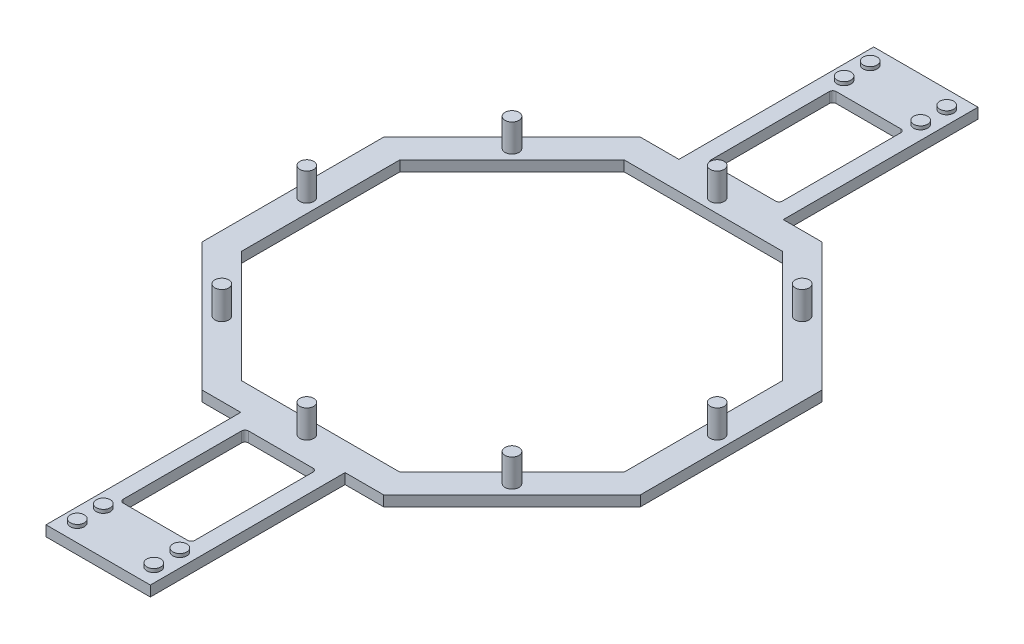
SolidWorks part; units mm, degrees
ref_plane "Front Plane" through (0, 0, 0) normal (0, 0, 1) x (1, 0, 0)
ref_plane "Top Plane" through (0, 0, 0) normal (0, 1, 0) x (1, 0, 0)
ref_plane "Right Plane" through (0, 0, 0) normal (1, 0, 0) x (0, 0, -1)
sketch "Sketch2" plane through (0, 0, 0) normal (0, 1, 0) x (1, 0, 0)
  line L0 (26.0955, 63) -> (15, 63)
  line L1 (22.7817, -55) -> (55, -22.7817)
  line L2 (55, -22.7817) -> (55, 22.7817)
  line L3 (55, 22.7817) -> (22.7817, 55)
  line L4 (22.7817, 55) -> (-22.7817, 55)
  line L5 (-22.7817, 55) -> (-55, 22.7817)
  line L6 (-55, 22.7817) -> (-55, -22.7817)
  line L7 (-55, -22.7817) -> (-22.7817, -55)
  line L8 (-22.7817, -55) -> (22.7817, -55)
  line L9 (-26.0955, 63) -> (-63, 26.0955)
  line L10 (-63, 26.0955) -> (-63, -26.0955)
  line L11 (-63, -26.0955) -> (-26.0955, -63)
  line L12 (-26.0955, -63) -> (-15, -63)
  line L13 (26.0955, -63) -> (63, -26.0955)
  line L14 (63, -26.0955) -> (63, 26.0955)
  line L15 (63, 26.0955) -> (26.0955, 63)
  line L16 (0, 63) -> (0, 55) construction
  line L17 (-15, 63) -> (-26.0955, 63)
  line L18 (15, 119) -> (-15, 119)
  line L19 (15, 119) -> (15, 63)
  line L20 (15, 55) -> (-15, 55)
  line L21 (-15, 119) -> (-15, 63)
  line L22 (-15, -119) -> (15, -119)
  line L25 (26.0955, 63) -> (-26.0955, 63) construction
  line L32 (-9.27, 102.507) -> (9.27, 102.507)
  line L33 (-10.27, 101.507) -> (-10.27, 67.507)
  line L34 (15, -119) -> (15, -63)
  line L35 (-9.27, 66.507) -> (9.27, 66.507)
  line L36 (10.27, 101.507) -> (10.27, 67.507)
  line L37 (-10.27, 102.507) -> (10.27, 66.507) construction
  line L38 (-10.27, 66.507) -> (10.27, 102.507) construction
  line L39 (-15, -119) -> (-15, -63)
  line L40 (-10.27, -101.507) -> (-10.27, -67.507)
  line L41 (9.27, -102.507) -> (-9.27, -102.507)
  line L42 (10.27, -101.507) -> (10.27, -67.507)
  line L43 (9.27, -66.507) -> (-9.27, -66.507)
  line L44 (15, -63) -> (26.0955, -63)
  line L45 (-15, 63) -> (15, 63) construction
  line L46 (-26.0955, -63) -> (26.0955, -63) construction
  circle A0 centre (0, 0) radius 55 construction
  arc A9 (-10.27, -67.507) -> (-9.27, -66.507) centre (-9.27, -67.507) cw
  arc A10 (10.27, -67.507) -> (9.27, -66.507) centre (9.27, -67.507) ccw
  arc A11 (9.27, -102.507) -> (10.27, -101.507) centre (9.27, -101.507) ccw
  arc A12 (-10.27, -101.507) -> (-9.27, -102.507) centre (-9.27, -101.507) ccw
  arc A13 (9.27, 66.507) -> (10.27, 67.507) centre (9.27, 67.507) ccw
  arc A14 (-10.27, 67.507) -> (-9.27, 66.507) centre (-9.27, 67.507) ccw
  arc A15 (9.27, 102.507) -> (10.27, 101.507) centre (9.27, 101.507) cw
  arc A16 (-9.27, 102.507) -> (-10.27, 101.507) centre (-9.27, 101.507) ccw
  point P21 (0, 84.507)
  point P29 (0, 87)
  point P60 (0, 0)
  point P97 (0, 0)
  dimension "D1" = 110
  dimension "D15" = 1
  dimension "D3" = 36
  dimension "D4" = 30
  dimension "D2" = 8
  dimension "D14" = 2
extrude "Boss-Extrude1" add sketch "Sketch2" along normal blind 3 contours L34 L44 L13 L14 L15 L0 L19 L18 L21 L17 L9 L10 L11 L12 L39 L22 A16 L32 A15 L36 A13 L35 A14 L33 A12 L40 A9 L43 A10 L42 A11 L41 L8 L7 L6 L5 L4 L3 L2 L1
sketch "Sketch3" plane through (0, 3, 0) normal (0, 1, 0) x (1, 0, 0)
  line L0 (15, 119) -> (-15, 119) construction
  line L1 (15, 119) -> (15, 63) construction
  line L2 (-15, 119) -> (-15, 63) construction
  circle A1 centre (-11, 114) radius 2
  circle A2 centre (-11, 106.5) radius 2
  circle A3 centre (11, 114) radius 2
  circle A4 centre (11, 106.5) radius 2
  circle A5 centre (11, -114) radius 2
  circle A6 centre (-11, -114) radius 2
  circle A7 centre (-11, -106.5) radius 2
  circle A8 centre (11, -106.5) radius 2
  point P25 (0, 0)
  dimension "D1" = 4
  dimension "D2" = 4
  dimension "D3" = 4
  dimension "D4" = 4
  dimension "D5" = 7.5
  dimension "D6" = 5
  dimension "D7" = 7.5
  dimension "D8" = 5
  dimension "D9" = 4
  dimension "D10" = 4
  dimension "D11" = 2
extrude "Boss-Extrude4" add sketch "Sketch3" along normal blind 1
sketch "Sketch5" plane through (0, 0, 0) normal (0, 1, 0) x (1, 0, 0)
  line L0 (-15, 63) -> (15, 63) construction
  line L1 (22.7817, 55) -> (-22.7817, 55) construction
  line L2 (0, 55) -> (0, 63) construction
  circle A2 centre (0, 59) radius 2
  circle A3 centre (41.7193, 41.7193) radius 2
  circle A4 centre (59, 0) radius 2
  circle A5 centre (41.7193, -41.7193) radius 2
  circle A6 centre (0, -59) radius 2
  circle A7 centre (-41.7193, -41.7193) radius 2
  circle A8 centre (-59, 0) radius 2
  circle A9 centre (-41.7193, 41.7193) radius 2
  point P26 (0, 0)
  dimension "D1" = 8
extrude "Boss-Extrude8" add sketch "Sketch5" along normal blind 11
